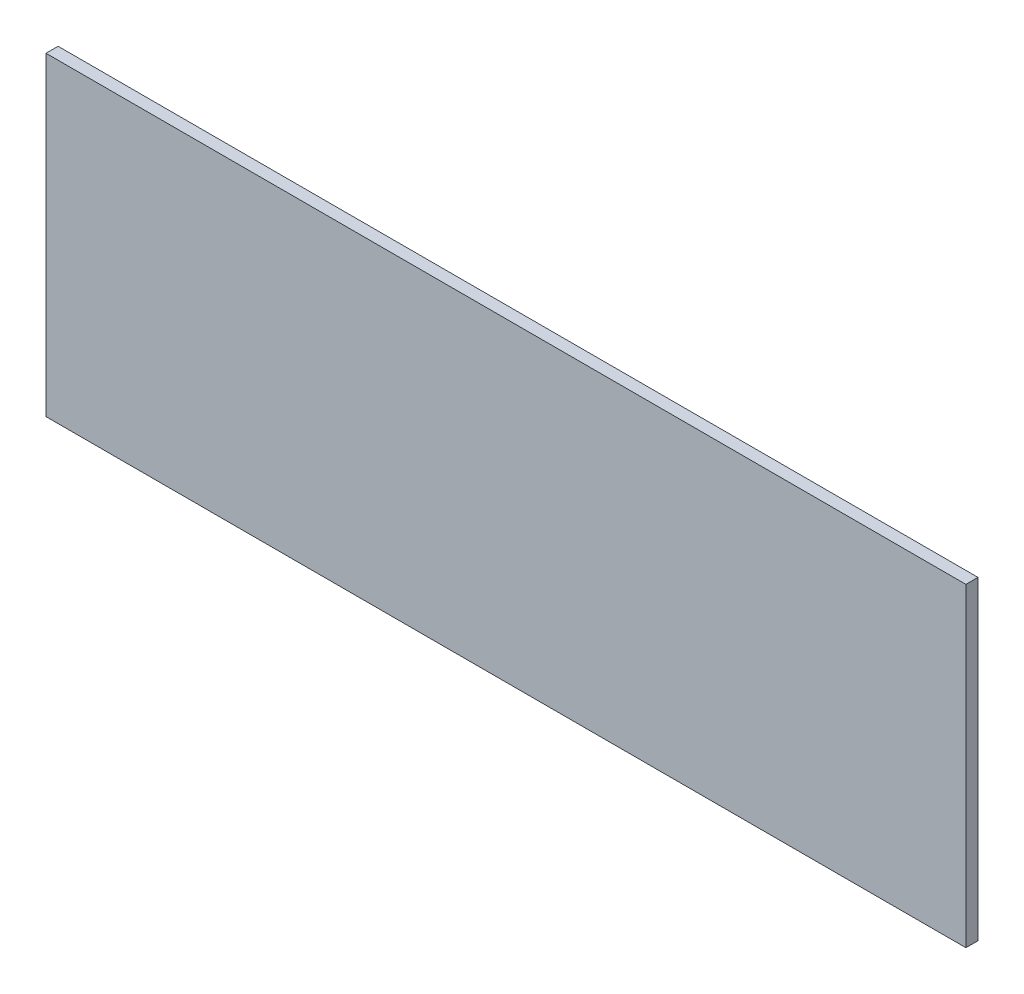
SolidWorks part; units mm, degrees
ref_plane "Front Plane" through (0, 0, 0) normal (0, 0, 1) x (1, 0, 0)
ref_plane "Top Plane" through (0, 0, 0) normal (0, 1, 0) x (1, 0, 0)
ref_plane "Right Plane" through (0, 0, 0) normal (1, 0, 0) x (0, 0, -1)
sketch "Sketch1" plane through (0, 0, 0) normal (0, 0, 1) x (1, 0, 0)
  line L1 (0, 0) -> (76, 0)
  line L2 (0, 0) -> (0, 26)
  line L3 (0, 26) -> (76, 26)
  line L4 (76, 0) -> (76, 26)
  dimension "D1" = 76
  dimension "D2" = 26
extrude "Boss-Extrude1" add sketch "Sketch1" along normal blind 1
